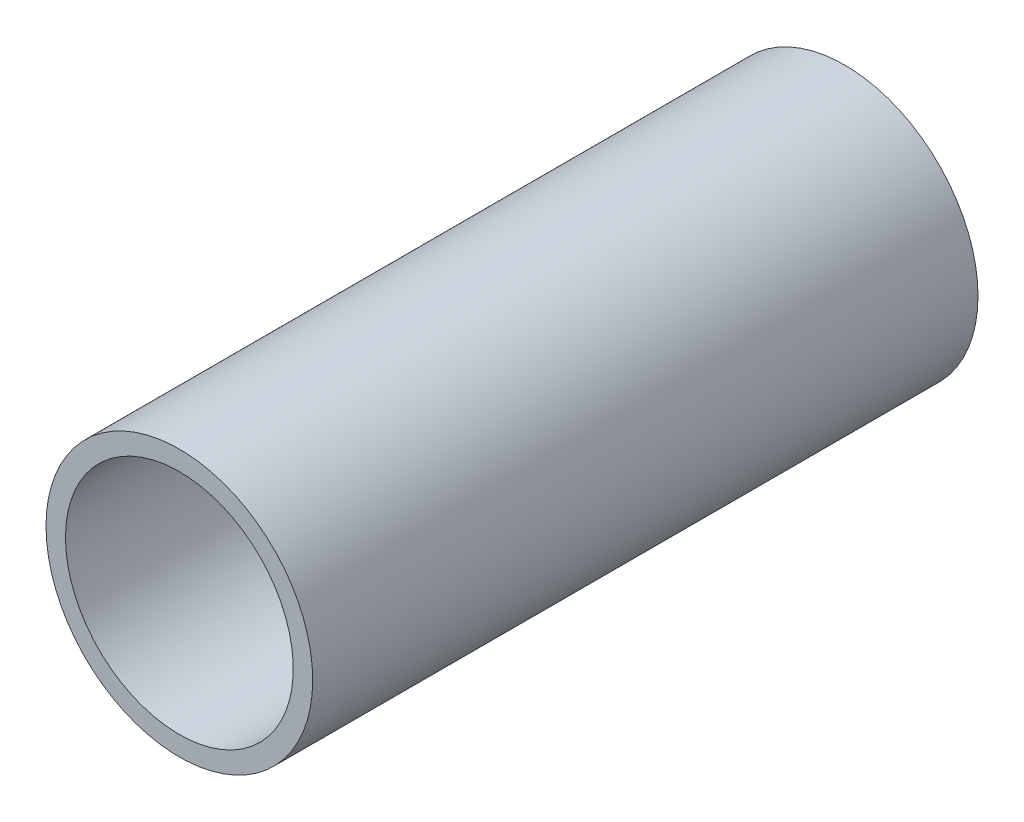
SolidWorks part; units mm, degrees
ref_plane "Front Plane" through (0, 0, 0) normal (0, 0, 1) x (1, 0, 0)
ref_plane "Top Plane" through (0, 0, 0) normal (0, 1, 0) x (1, 0, 0)
ref_plane "Right Plane" through (0, 0, 0) normal (1, 0, 0) x (0, 0, -1)
sketch "Sketch1" plane through (0, 0, 0) normal (0, 0, 1) x (1, 0, 0)
  circle A0 centre (0, 0) radius 44.7
  circle A1 centre (0, 0) radius 38.17
extrude "Boss-Extrude1" add sketch "Sketch1" along normal blind 223
